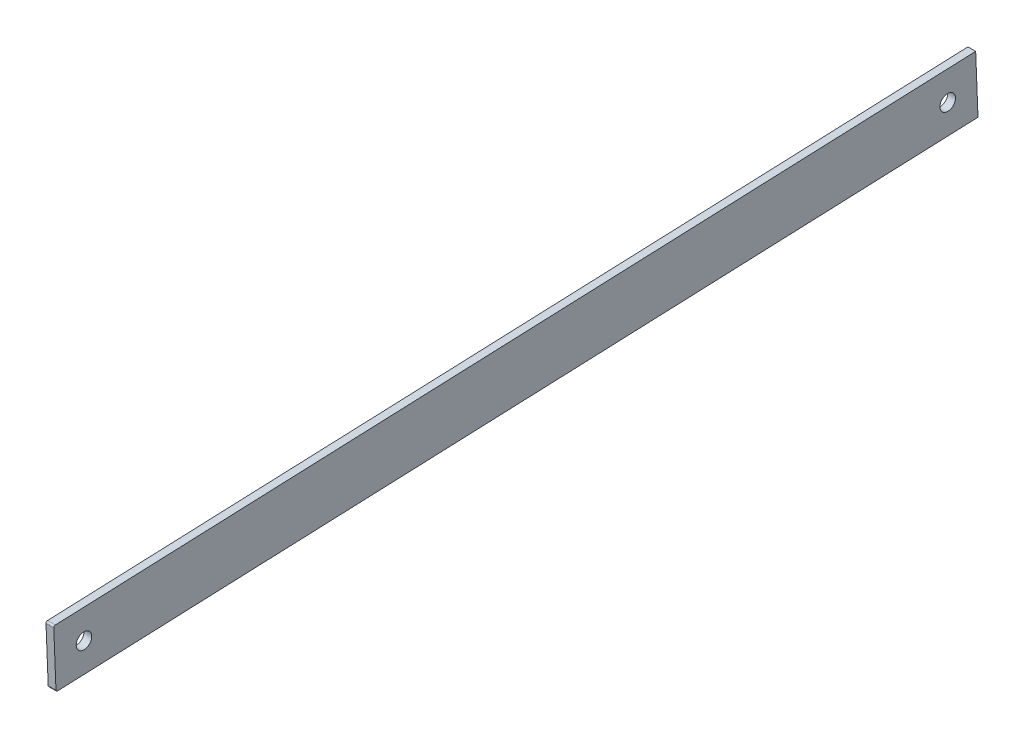
SolidWorks part; units mm, degrees
ref_plane "Front Plane" through (0, 0, 0) normal (0, 0, 1) x (1, 0, 0)
ref_plane "Top Plane" through (0, 0, 0) normal (0, 1, 0) x (1, 0, 0)
ref_plane "Right Plane" through (0, 0, 0) normal (1, 0, 0) x (0, 0, -1)
ref_plane "Plane1" through (1.4, 0, 0) normal (-1, 0, 0) x (0, -1, 0)
sketch "Sketch1" plane through (1.4, 0, 0) normal (-1, 0, 0) x (0, -1, 0)
  line L0 (-254.7391, 199.3758) -> (-224.7628, 198.1828)
  line L1 (-224.7628, 198.1828) -> (-205.9083, 671.9657)
  line L2 (-206.7162, 672.8406) -> (-235.0096, 673.9666)
  line L3 (-235.8845, 673.1587) -> (-254.7391, 199.3758)
  arc A0 (-206.7162, 672.8406) -> (-205.9083, 671.9657) centre (-206.7497, 671.9992) cw
  arc A1 (-235.8845, 673.1587) -> (-235.0096, 673.9666) centre (-235.0431, 673.1252) cw
  circle A2 centre (-221.4594, 658.4155) radius 4
  circle A3 centre (-239.1545, 213.7674) radius 4
  dimension "D7" = 8
  dimension "D1" = 475
  dimension "D2" = 15
  dimension "D3" = 15
  dimension "D4" = 30
  dimension "D5" = 15
  dimension "D6" = 15
extrude "Boss-Extrude1" add sketch "Sketch1" against normal blind 4
